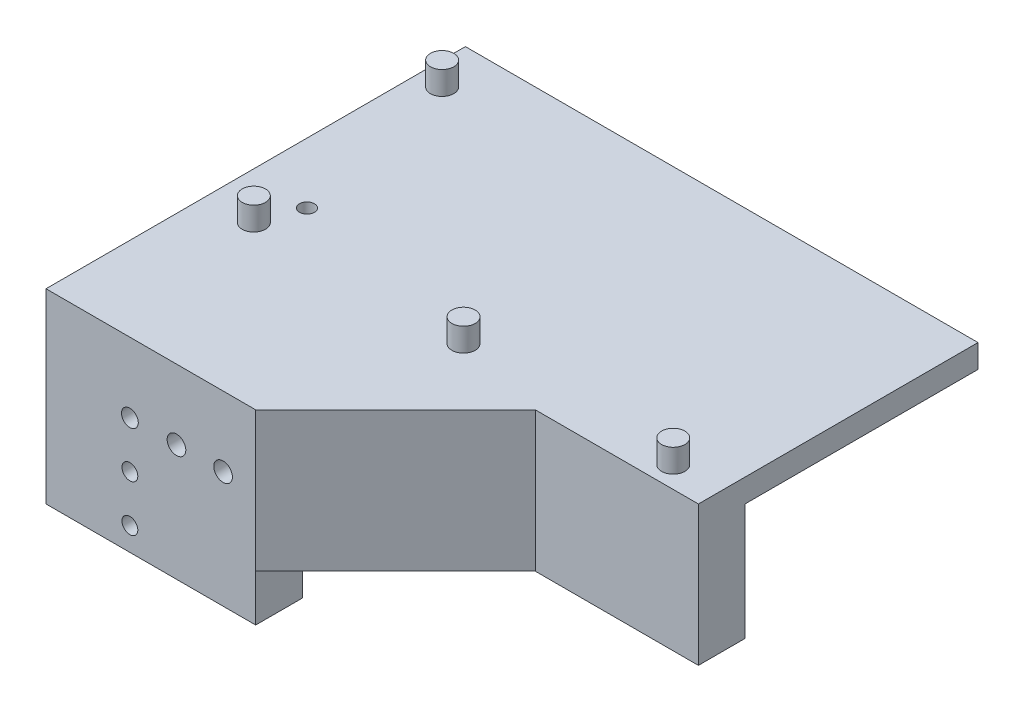
SolidWorks part; units mm, degrees
ref_plane "Front Plane" through (0, 0, 0) normal (0, 0, 1) x (1, 0, 0)
ref_plane "Top Plane" through (0, 0, 0) normal (0, 1, 0) x (1, 0, 0)
ref_plane "Right Plane" through (0, 0, 0) normal (1, 0, 0) x (0, 0, -1)
sketch "Sketch1" plane through (0, 0, 0) normal (0, 1, 0) x (1, 0, 0)
  line L0 (-69.85, -38.1) -> (69.85, -38.1)
  line L1 (-69.85, -38.1) -> (-69.85, 38.1)
  line L2 (69.85, -38.1) -> (69.85, 38.1)
  line L3 (-69.85, 38.1) -> (69.85, 38.1)
  line L4 (-69.85, -38.1) -> (69.85, 38.1) construction
  line L5 (69.85, -38.1) -> (-69.85, 38.1) construction
  point P1 (0, 0)
  dimension "D1" = 139.7
  dimension "D2" = 76.2
extrude "Boss-Extrude1" add sketch "Sketch1" against normal blind 38.1
sketch "Sketch2" plane through (0, -38.1, 0) normal (0, -1, 0) x (1, 0, 0)
  line L0 (69.85, 25.4) -> (7.62, 25.4)
  line L1 (69.85, 38.1) -> (69.85, -38.1) construction
  line L2 (7.62, 25.4) -> (7.62, 0)
  line L3 (7.62, 0) -> (-58.42, 0)
  line L4 (-58.42, 0) -> (-58.42, -38.1)
  line L5 (69.85, -38.1) -> (-69.85, -38.1) construction
  line L6 (-69.85, 38.1) -> (69.85, 38.1) construction
  line L7 (-69.85, -38.1) -> (-69.85, 38.1) construction
  dimension "D1" = 12.7
  dimension "D2" = 77.47
  dimension "D3" = 38.1
  dimension "D4" = 11.43
extrude "Cut-Extrude1" cut sketch "Sketch2" against normal blind 31.75 and the other way through all
sketch "Sketch3" plane through (0, -38.1, 0) normal (0, -1, 0) x (1, 0, 0)
  line L0 (-69.85, -38.1) -> (-69.85, 38.1) construction
  line L1 (-69.85, 38.1) -> (69.85, 38.1) construction
  circle A0 centre (-53.34, 21.59) radius 2.032
  dimension "D1" = 4.064
  dimension "D2" = 16.51
  dimension "D3" = 16.51
extrude "Cut-Extrude2" cut sketch "Sketch3" against normal through all
sketch "Sketch4" plane through (0, 0, 0) normal (0, 0, -1) x (-1, 0, 0)
  line L0 (-7.62, -38.1) -> (-7.62, -6.35) construction
  line L1 (58.42, -6.35) -> (6.35, -6.35)
  line L2 (58.42, -6.35) -> (58.42, -31.75)
  line L3 (58.42, -31.75) -> (6.35, -31.75)
  line L4 (6.35, -6.35) -> (6.35, -31.75)
  line L5 (-7.62, -38.1) -> (58.42, -38.1) construction
  dimension "D1" = 13.97
  dimension "D2" = 6.35
extrude "Cut-Extrude3" cut sketch "Sketch4" against normal blind 10.414
sketch "Sketch7" plane through (0, 0, 38.1) normal (0, 0, 1) x (1, 0, 0)
  line L1 (-69.85, 0) -> (-12.7, 0)
  line L2 (-69.85, 0) -> (-69.85, -12.7)
  line L3 (-69.85, -12.7) -> (-12.7, -12.7)
  line L4 (-12.7, 0) -> (-12.7, -12.7)
  dimension "D1" = 57.15
  dimension "D2" = 12.7
extrude "Boss-Extrude2" add sketch "Sketch7" along normal blind 25.4
sketch "Sketch8" plane through (0, 0, 63.5) normal (0, 0, 1) x (1, 0, 0)
  line L1 (-69.85, 0) -> (-12.7, 0)
  line L2 (-69.85, 0) -> (-69.85, -50.8)
  line L3 (-69.85, -50.8) -> (-12.7, -50.8)
  line L4 (-12.7, 0) -> (-12.7, -50.8)
  dimension "D1" = 50.8
  dimension "D2" = 57.15
extrude "Boss-Extrude3" add sketch "Sketch8" along normal blind 12.7
sketch "Sketch5" plane through (0, 0, 10.414) normal (0, 0, -1) x (-1, 0, 0)
  line L0 (58.42, -31.75) -> (58.42, -6.35) construction
  line L1 (6.35, -31.75) -> (58.42, -31.75) construction
  circle A0 centre (46.99, -19.05) radius 2.286
  circle A1 centre (34.29, -19.05) radius 2.54
  circle A2 centre (21.59, -19.05) radius 2.54
  dimension "D1" = 4.572
  dimension "D4" = 12.7
  dimension "D6" = 5.08
  dimension "D2" = 11.43
  dimension "D3" = 12.7
  dimension "D5" = 12.7
extrude "Cut-Extrude4" cut sketch "Sketch5" against normal through all
sketch "Sketch6" plane through (0, 0, 10.414) normal (0, 0, -1) x (-1, 0, 0)
  line L0 (27.051, -18.288) -> (26.6125, -18.288)
  line L1 (27.051, -21.082) -> (28.829, -21.082)
  line L2 (27.051, -21.082) -> (27.051, -19.812)
  line L3 (27.051, -17.018) -> (28.829, -17.018)
  line L4 (28.829, -21.082) -> (28.829, -19.812)
  line L5 (27.051, -21.082) -> (28.829, -17.018) construction
  line L6 (27.051, -17.018) -> (28.829, -21.082) construction
  line L7 (27.051, -19.812) -> (26.6125, -19.812)
  line L8 (28.829, -19.812) -> (29.2675, -19.812)
  line L9 (28.829, -18.288) -> (29.2675, -18.288)
  line L10 (28.829, -18.288) -> (28.829, -17.018)
  line L11 (27.051, -18.288) -> (27.051, -17.018)
  arc A0 (29.2675, -19.812) -> (29.2675, -18.288) centre (34.29, -19.05) ccw
  arc A1 (26.6125, -18.288) -> (26.6125, -19.812) centre (21.59, -19.05) ccw
  point P6 (27.94, -19.05)
  dimension "D1" = 10.16
  dimension "D2" = 1.778
  dimension "D3" = 4.064
  dimension "D4" = 1.27
extrude "Cut-Extrude5" cut sketch "Sketch6" against normal blind 14.986
sketch "Sketch9" plane through (0, 0, 63.5) normal (0, 0, -1) x (-1, 0, 0)
  line L0 (46.99, -19.05) -> (46.99, -50019.05) construction
  line L1 (69.85, -50.8) -> (12.7, -50.8) construction
  line L2 (42.3232, -16.8654) -> (42.3232, -46.6346)
  line L3 (44.704, -14.224) -> (42.3232, -16.8654)
  line L4 (51.6568, -16.8654) -> (51.6568, -46.6346)
  line L5 (42.3232, -31.75) -> (51.6568, -31.75) construction
  line L6 (49.276, -49.276) -> (44.704, -49.276)
  line L7 (51.6568, -16.8654) -> (49.276, -14.224)
  line L8 (49.276, -14.224) -> (44.704, -14.224)
  line L9 (51.6568, -46.6346) -> (49.276, -49.276)
  line L10 (44.704, -49.276) -> (42.3232, -46.6346)
  circle A1 centre (46.99, -19.05) radius 2.286 construction
  point P5 (46.99, -14.224)
  dimension "D1" = 90
  dimension "D5" = 3.556
  dimension "D6" = 4.826
  dimension "D2" = 4.572
  dimension "D3" = 47.97
  dimension "D4" = 35.052
extrude "Cut-Extrude6" cut sketch "Sketch9" against normal blind 7.112
sketch "Sketch10" plane through (0, 0, 70.612) normal (0, 0, -1) x (-1, 0, 0)
  line L0 (46.99, -49.276) -> (46.99, -14.224) construction
  line L1 (44.704, -49.276) -> (49.276, -49.276) construction
  line L2 (49.276, -14.224) -> (44.704, -14.224) construction
  line L3 (46.99, -19.05) -> (40.64, -19.05) construction
  line L4 (46.99, -19.05) -> (46.99, -30.0482) construction
  circle A0 centre (46.99, -19.05) radius 2.159
  circle A3 centre (46.99, -31.75) radius 2.159
  circle A6 centre (46.99, -44.45) radius 2.159
  circle A9 centre (46.99, -31.75) radius 2.159 [skipped]
  circle A10 centre (46.99, -19.05) radius 2.159 [skipped]
  circle A11 centre (46.99, -19.05) radius 2.159 [skipped]
  circle A12 centre (46.99, -31.75) radius 2.159 [skipped]
  circle A13 centre (46.99, -44.45) radius 2.159 [skipped]
  circle A14 centre (46.99, -44.45) radius 2.159 [skipped]
  dimension "D1" = 3
  dimension "D4" = 4.318
  dimension "D2" = 90
  dimension "D3" = 3
extrude "Cut-Extrude7" cut sketch "Sketch10" against normal through all
sketch "Sketch11" plane through (0, 0, 0) normal (0, 0, -1) x (-1, 0, 0)
  line L1 (58.42, -38.1) -> (6.35, -38.1)
  line L2 (58.42, -38.1) -> (58.42, -31.75)
  line L3 (58.42, -31.75) -> (6.35, -31.75)
  line L4 (6.35, -38.1) -> (6.35, -31.75)
extrude "Boss-Extrude4" add sketch "Sketch11" along normal blind 25.4
sketch "Sketch14" plane through (0, 0, 0) normal (0, 1, 0) x (1, 0, 0)
  line L0 (-12.7, -76.2) -> (25.4, -38.1)
  line L1 (-12.7, -38.1) -> (69.85, -38.1) construction
  line L2 (-12.7, -76.2) -> (-12.7, -38.1) construction
  line L3 (-12.7, -76.2) -> (-12.7, -38.1)
  line L4 (-12.7, -38.1) -> (25.4, -38.1)
  dimension "D1" = 45
extrude "Boss-Extrude5" add sketch "Sketch14" against normal blind 38.1
sketch "Sketch15" plane through (0, -38.1, 0) normal (0, -1, 0) x (1, 0, 0)
  line L5 (69.85, 38.1) -> (69.85, 25.4) construction
  line L6 (-69.85, 38.1) -> (-12.7, 38.1) construction
  circle A0 centre (57.15, 31.75) radius 3.175
  circle A1 centre (0.0009, 32.0675) radius 3.175
  circle A2 centre (-57.1482, 32.385) radius 3.175
  point P5 (69.85, 31.75)
  dimension "D3" = 3
  dimension "D5" = 5.715
  dimension "D1" = 6.35
  dimension "D2" = 12.7
  dimension "D4" = 57.15
extrude "Cut-Extrude8" cut sketch "Sketch15" against normal blind 6.35
sketch "Sketch16" plane through (0, 0, 0) normal (0, 1, 0) x (1, 0, 0)
  line L0 (25.4, -38.1) -> (69.85, -38.1) construction
  line L1 (69.85, -38.1) -> (69.85, 38.1) construction
  line L2 (-12.7, -76.2) -> (-69.85, -76.2) construction
  line L3 (69.85, 38.1) -> (-69.85, 38.1) construction
  line L4 (-69.85, 38.1) -> (-69.85, -76.2) construction
  circle A0 centre (57.15, -32.258) radius 3.175
  circle A1 centre (0, -32.258) radius 3.175
  circle A2 centre (-57.15, -32.258) radius 3.175
  circle A3 centre (-63.5, 25.4) radius 3.175
  dimension "D2" = 6.35
  dimension "D5" = 57.15
  dimension "D9" = 6.35
  dimension "D1" = 5.842
  dimension "D3" = 12.7
  dimension "D6" = 43.942
  dimension "D7" = 12.7
  dimension "D8" = 6.35
  dimension "D4" = 3
extrude "Boss-Extrude6" add sketch "Sketch16" along normal blind 6.35
